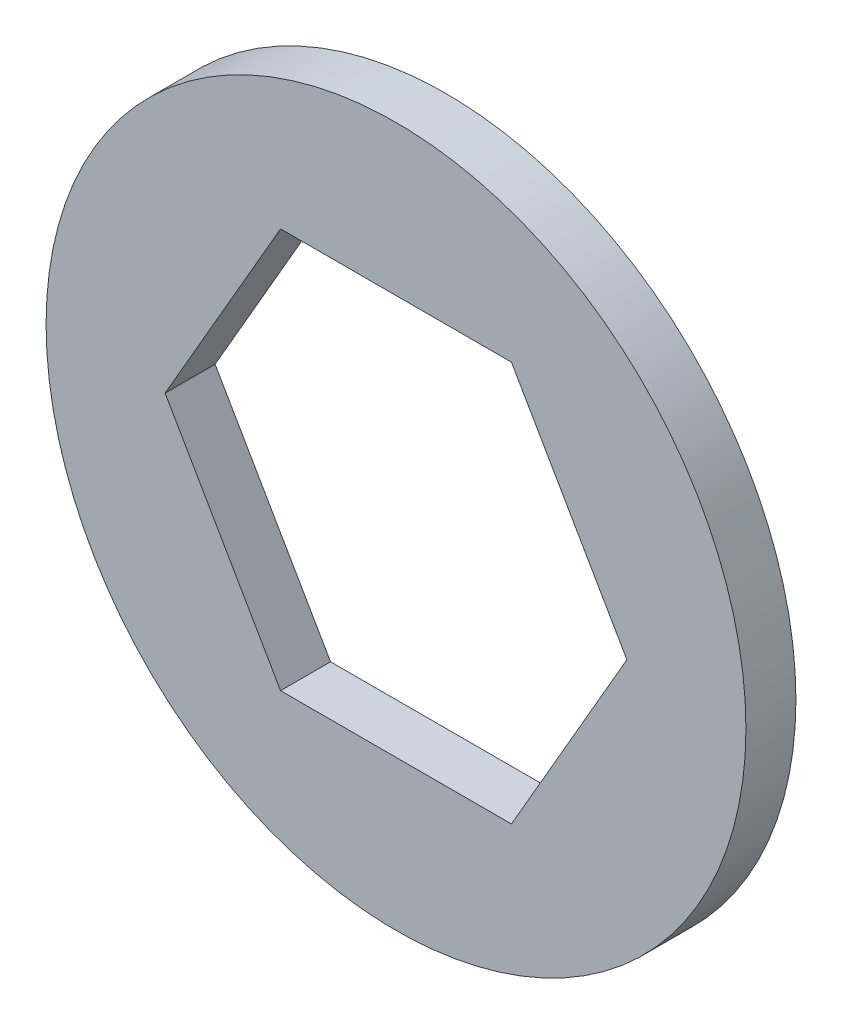
SolidWorks part; units mm, degrees
material "Nylon 101"
ref_plane "Front Plane" through (0, 0, 0) normal (0, 0, 1) x (1, 0, 0)
ref_plane "Top Plane" through (0, 0, 0) normal (0, 1, 0) x (1, 0, 0)
ref_plane "Right Plane" through (0, 0, 0) normal (1, 0, 0) x (0, 0, -1)
sketch "Sketch1" plane through (0, 0, 0) normal (0, 0, 1) x (1, 0, 0)
  line L1 (3.6662, 6.35) -> (-3.6662, 6.35)
  line L2 (-3.6662, 6.35) -> (-7.3323, 0)
  line L3 (-7.3323, 0) -> (-3.6662, -6.35)
  line L4 (-3.6662, -6.35) -> (3.6662, -6.35)
  line L5 (3.6662, -6.35) -> (7.3323, 0)
  line L6 (7.3323, 0) -> (3.6662, 6.35)
  circle A0 centre (0, 0) radius 6.35 construction
  circle A1 centre (0, 0) radius 11.1125
  point P1 (0, 6.35)
  dimension "D1" = 12.7
  dimension "D2" = 22.225
extrude "Boss-Extrude1" add sketch "Sketch1" along normal blind 1.5875
